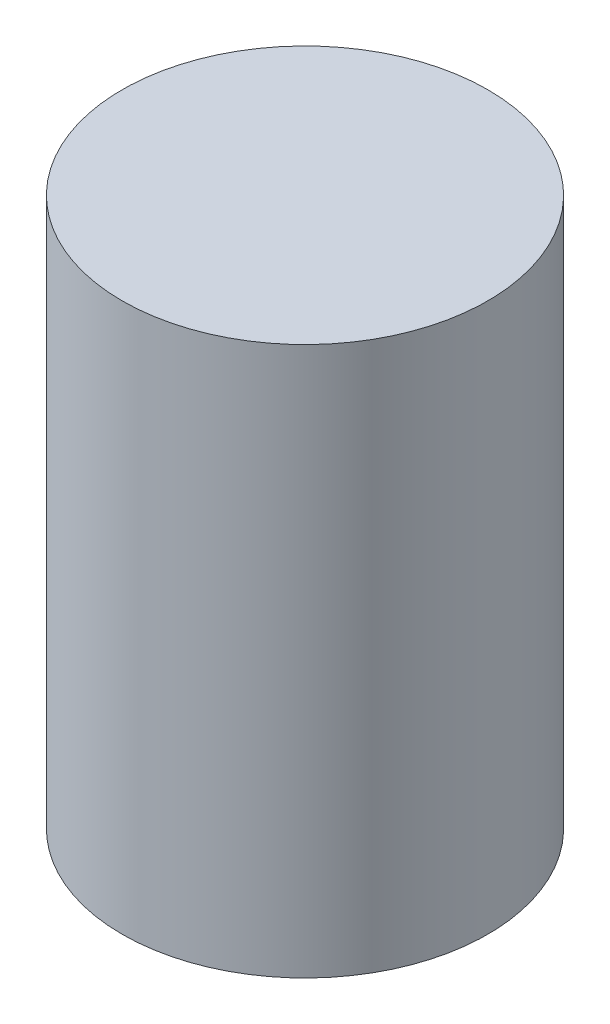
SolidWorks part; units mm, degrees
ref_plane "Front Plane" through (0, 0, 0) normal (0, 0, 1) x (1, 0, 0)
ref_plane "Top Plane" through (0, 0, 0) normal (0, 1, 0) x (1, 0, 0)
ref_plane "Right Plane" through (0, 0, 0) normal (1, 0, 0) x (0, 0, -1)
sketch "Sketch1" plane through (0, 0, 0) normal (0, 1, 0) x (1, 0, 0)
  circle A0 centre (0, 0) radius 12.7
  dimension "D1" = 25.4
extrude "Boss-Extrude1" add sketch "Sketch1" along normal blind 38.1 contours A0
